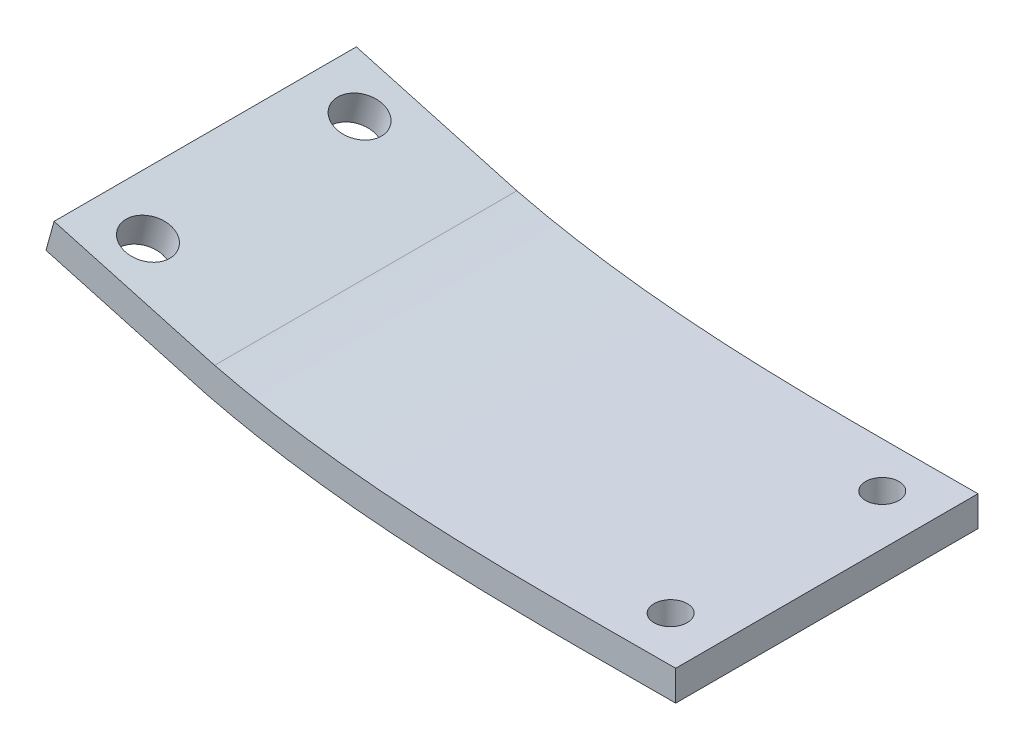
SolidWorks part; units mm, degrees
ref_plane "Piano frontale" through (0, 0, 0) normal (0, 0, 1) x (1, 0, 0)
ref_plane "Piano superiore" through (0, 0, 0) normal (0, 1, 0) x (1, 0, 0)
ref_plane "Piano destro" through (0, 0, 0) normal (1, 0, 0) x (0, 0, -1)
sketch "Schizzo1" plane through (0, 0, 0) normal (0, 0, 1) x (1, 0, 0)
  line L0 (0, 0) -> (150, 0)
  line L1 (150, 0) -> (94.2149, 0.9737) construction
  line L2 (150, 0) -> (78.851, 2.4846) construction
  line L3 (150, 0) -> (66.9131, 4.3544) construction
  line L4 (150, 0) -> (56.9541, 6.5064) construction
  line L5 (150, 0) -> (25.0148, 15.3463) construction
  line L6 (-299.0536, -537.5076) -> (-1111.2465, -622.8725) construction
  line L7 (25.0148, 15.3463) -> (56.9541, 6.5064)
  line L8 (26.6152, 21.1289) -> (58.4735, 12.3114)
  line L9 (149.9926, 6) -> (150, 0)
  line L10 (25.0148, 15.3463) -> (26.6152, 21.1289)
  spline S0 degree 3 poles (150, 0) (126.3707, -0.029) (94.9081, -0.7051) (64.164, 4.725) (56.9541, 6.5064) knots 0 0 0 0 0.761804 1 1 1 1
  spline S1 degree 1 poles (149.9926, 6) (58.4735, 12.3114) knots 0 0 1 1 construction
  spline S2 degree 3 poles (58.4735, 12.3114) (62.1265, 11.4109) (69.481, 9.8709) (84.4753, 7.647) (103.508, 6.2193) (126.6665, 5.8672) (142.2274, 5.9905) (149.9926, 6) knots 0 0 0 0 0.124885 0.249771 0.499542 0.749313 0.999084 0.999084 0.999084 0.999084
  dimension "D1" = 150
  dimension "D2" = 1
  dimension "D3" = 1
  dimension "D4" = 1
  dimension "D5" = 1
  dimension "D6" = 3
  dimension "D7" = 10.1888
  dimension "D8" = 12.0835
  dimension "D9" = 15.438
  dimension "D10" = 6
extrude "Estrusione-Estrusione1" add sketch "Schizzo1" against normal blind 60 contours S0 L7 L10 L8 S2 L9
ref_plane "Piano1" through (0, 6, 0) normal (0, 1, 0) x (1, 0, 0)
sketch "Schizzo2" plane through (0, 6, 0) normal (0, 1, 0) x (1, 0, 0)
  line L0 (139.9926, 69.5854) -> (139.9926, -19.791) construction
  line L1 (5.6305, 51) -> (178.662, 51) construction
  line L2 (149.9926, 60) -> (58.4735, 60) construction
  line L3 (149.9926, 60) -> (149.9926, 0) construction
  line L4 (149.9926, 30) -> (10.5787, 30) construction
  circle A0 centre (139.9926, 51) radius 3.3
  circle A1 centre (139.9926, 9) radius 3.3
  point P12 (0, 0)
  dimension "D3" = 6.6
  dimension "D1" = 9
  dimension "D2" = 10
extrude "Taglio-Estrusione1" cut sketch "Schizzo2" against normal through all
sketch "Schizzo3" plane through (7.3255, 26.4677, 0) normal (0.2667, 0.9638, 0) x (0.9638, -0.2667, 0)
  line L0 (30.0149, 64.9395) -> (30.0149, -8.2062) construction
  line L1 (13.2253, 51) -> (39.3589, 51) construction
  line L2 (20.0149, 60) -> (20.0149, 0) construction
  line L3 (20.0149, 60) -> (53.0709, 60) construction
  line L4 (20.0149, 30) -> (79.9795, 30) construction
  circle A0 centre (30.0149, 51) radius 4.5
  circle A1 centre (30.0149, 9) radius 4.5
  dimension "D1" = 9
  dimension "D2" = 10
  dimension "D3" = 9
extrude "Taglio-Estrusione2" cut sketch "Schizzo3" against normal through all
